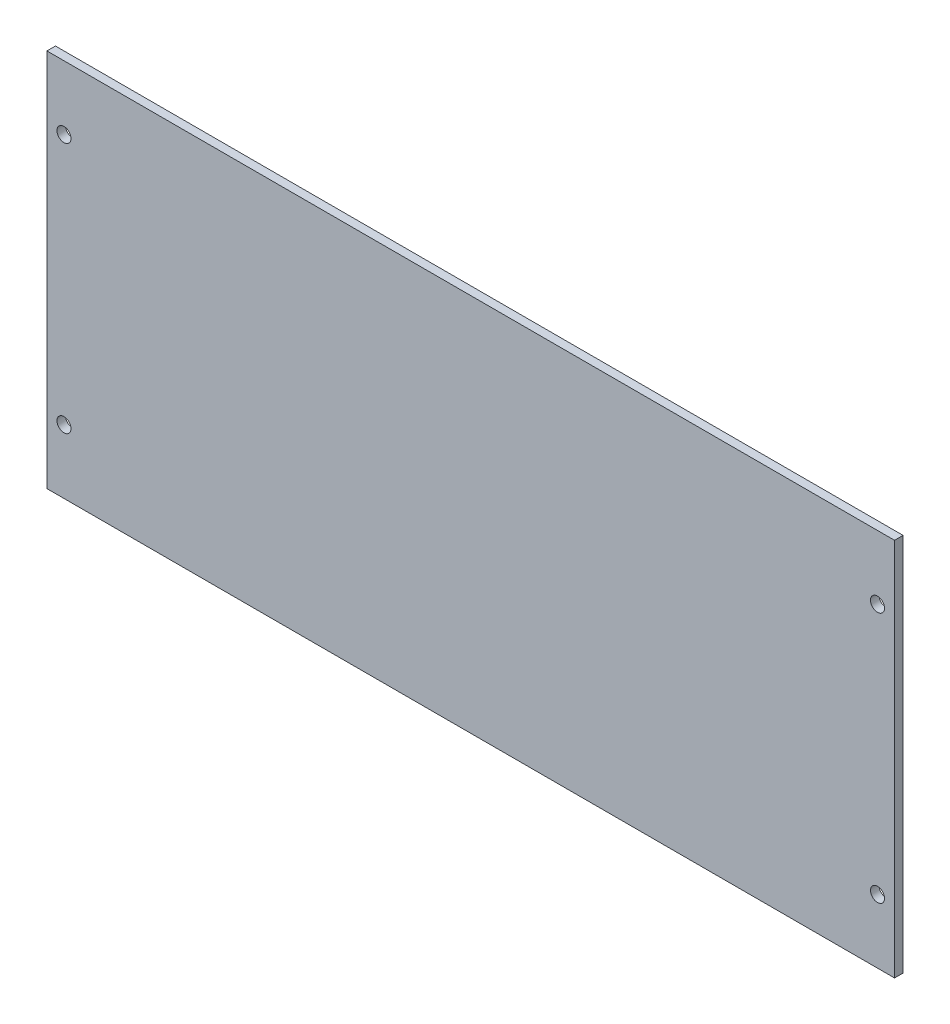
SolidWorks part; units mm, degrees
ref_plane "Plan de face" through (0, 0, 0) normal (0, 0, 1) x (1, 0, 0)
ref_plane "Plan de dessus" through (0, 0, 0) normal (0, 1, 0) x (1, 0, 0)
ref_plane "Plan de droite" through (0, 0, 0) normal (1, 0, 0) x (0, 0, -1)
sketch "Esquisse1" plane through (0, 0, 0) normal (0, 0, 1) x (1, 0, 0)
  line L1 (-199, -89) -> (199, -89)
  line L2 (-199, -89) -> (-199, 89)
  line L3 (-199, 89) -> (199, 89)
  line L4 (199, -89) -> (199, 89)
  line L5 (-199, -89) -> (199, 89) construction
  line L6 (-199, 89) -> (199, -89) construction
  point P0 (0, 0)
  dimension "D1" = 398
  dimension "D2" = 178
extrude "Boss.-Extru.1" add sketch "Esquisse1" along normal blind 4
hole_wizard "Dégagement M61" positions "Esquisse3" profile "Esquisse2" hole size "M6" standard "ISO" end condition through all
sketch "Esquisse3" plane through (0, 0, 0) normal (0, 0, -1) x (-1, 0, 0)
  line L1 (-191, -81) -> (191, -81) construction
  line L2 (-191, -81) -> (-191, 81) construction
  line L3 (-191, 81) -> (191, 81) construction
  line L4 (191, -81) -> (191, 81) construction
  line L5 (-191, -81) -> (191, 81) construction
  line L6 (-191, 81) -> (191, -81) construction
  line L7 (-199, 89) -> (199, 89) construction
  line L9 (0, 153.0002) -> (0, -160.7922) construction
  line L11 (-248.73, 0) -> (316.3802, 0) construction
  line L12 (199, 89) -> (199, -89) construction
  line L13 (199, -89) -> (-199, -89) construction
  point P6 (191, 59)
  point P8 (-191, 59)
  point P156 (191, -59)
  point P158 (-191, -59)
  dimension "D1" = 8
  dimension "D4" = 8
  dimension "D5" = 8
  dimension "D6" = 30
sketch "Esquisse2" plane through (-191, 59, 0) normal (1, 0, 0) x (0, 1, 0)
  line L0 (0, 0) -> (0, 4)
  line L1 (0, 4) -> (3.3, 4)
  line L2 (3.3, 4) -> (3.3, 0)
  line L5 (3.3, 0) -> (0, 0)
  line L11 (0, -6.35) -> (0, 107.95) construction
  dimension "Diamètre du perçage jusqu'au prochain" = 6.6
  dimension "Profondeur du perçage jusqu'au prochain" = 4
